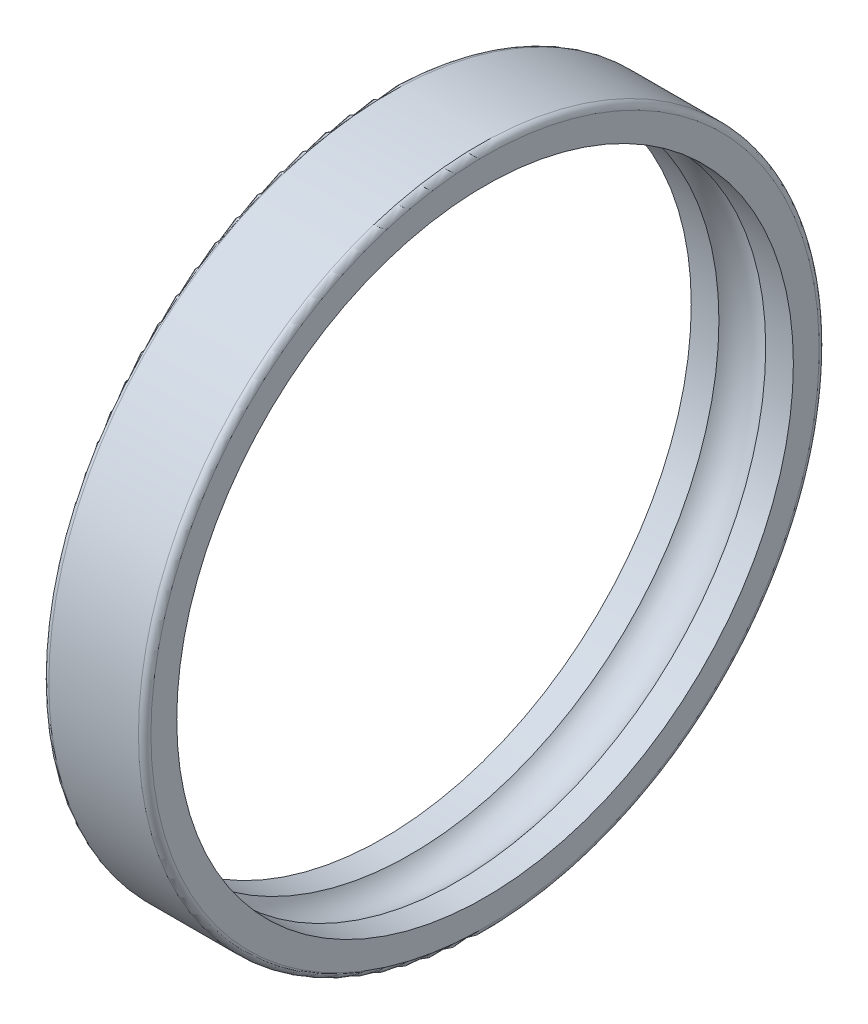
SolidWorks part; units mm, degrees
ref_plane "Piano frontale" through (0, 0, 0) normal (0, 0, 1) x (1, 0, 0)
ref_plane "Piano superiore" through (0, 0, 0) normal (0, 1, 0) x (1, 0, 0)
ref_plane "Piano destro" through (0, 0, 0) normal (1, 0, 0) x (0, 0, -1)
ref_plane "Piano1" through (0, 0, 0) normal (0, 0, 1) x (1, 0, 0)
sketch "Schizzo1" plane through (0, 0, 0) normal (0, 0, 1) x (1, 0, 0)
  line L0 (0, 58.9) -> (0, 54.35)
  line L1 (0, 54.35) -> (4.8756, 54.35)
  line L2 (13.1244, 54.35) -> (18, 54.35)
  line L3 (18, 54.35) -> (18, 58.9)
  line L4 (16.9, 60) -> (1.1, 60)
  line L5 (200, 0) -> (-200, 0) construction
  arc A0 (4.8756, 54.35) -> (13.1244, 54.35) centre (9, 51.25) cw
  arc A1 (18, 58.9) -> (16.9, 60) centre (16.9, 58.9) ccw
  arc A2 (1.1, 60) -> (0, 58.9) centre (1.1, 58.9) ccw
revolve "Rivoluzione1" add sketch "Schizzo1" angle 360 about L5
